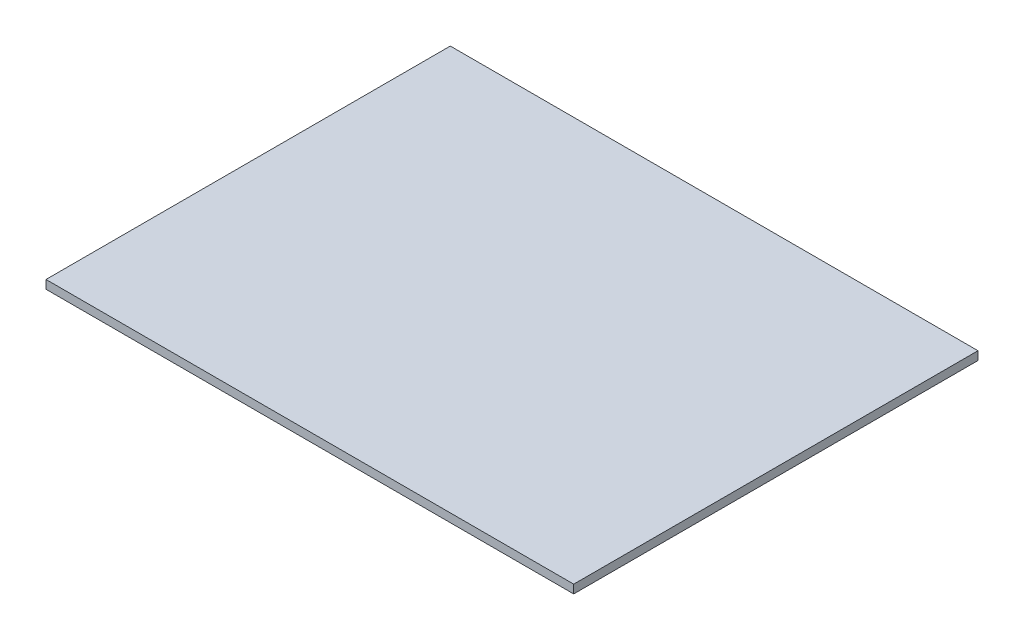
SolidWorks part; units mm, degrees
ref_plane "Front Plane" through (0, 0, 0) normal (0, 0, 1) x (1, 0, 0)
ref_plane "Top Plane" through (0, 0, 0) normal (0, 1, 0) x (1, 0, 0)
ref_plane "Right Plane" through (0, 0, 0) normal (1, 0, 0) x (0, 0, -1)
sketch "Sketch1" plane through (0, 0, 0) normal (0, 1, 0) x (1, 0, 0)
  line L1 (-248, -190) -> (248, -190)
  line L2 (-248, -190) -> (-248, 190)
  line L3 (-248, 190) -> (248, 190)
  line L4 (248, -190) -> (248, 190)
  line L5 (-248, -190) -> (248, 190) construction
  line L6 (-248, 190) -> (248, -190) construction
  point P0 (0, 0)
  dimension "D1" = 496
  dimension "D2" = 380
extrude "Boss-Extrude1" add sketch "Sketch1" along normal blind 8
